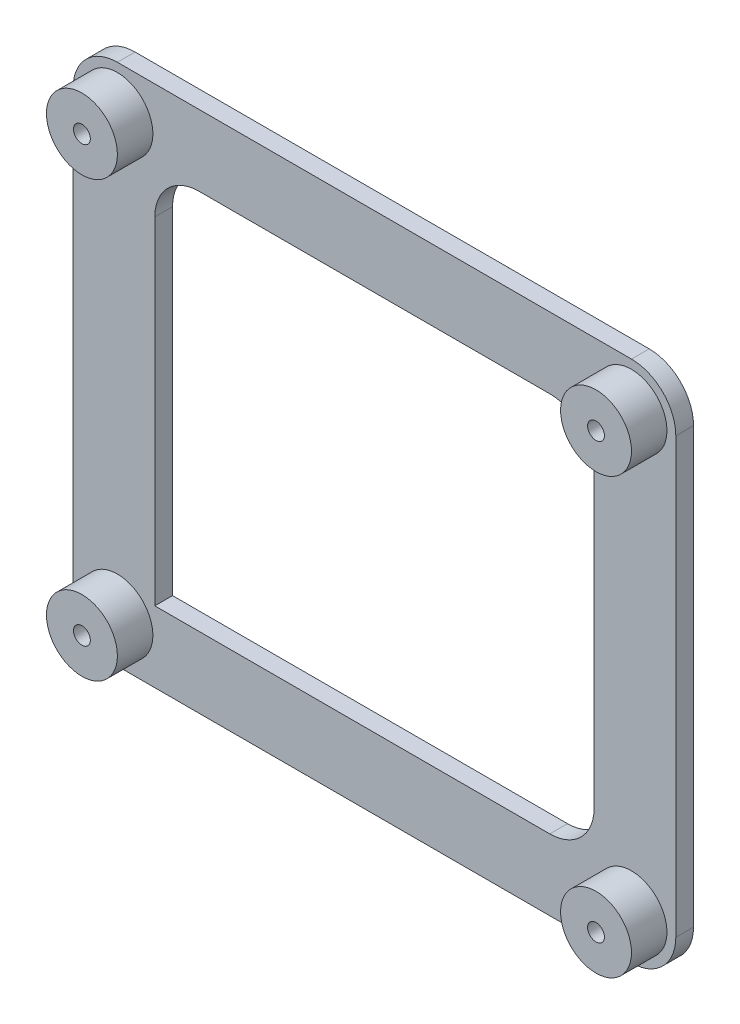
SolidWorks part; units mm, degrees
ref_plane "Front Plane" through (0, 0, 0) normal (0, 0, 1) x (1, 0, 0)
ref_plane "Top Plane" through (0, 0, 0) normal (0, 1, 0) x (1, 0, 0)
ref_plane "Right Plane" through (0, 0, 0) normal (1, 0, 0) x (0, 0, -1)
sketch "Sketch1" plane through (0, 0, 0) normal (0, 0, 1) x (1, 0, 0)
  line L1 (-29, -24.5) -> (29, -24.5) construction
  line L2 (-29, -24.5) -> (-29, 24.5) construction
  line L3 (-29, 24.5) -> (29, 24.5) construction
  line L4 (29, -24.5) -> (29, 24.5) construction
  line L5 (-29, -24.5) -> (29, 24.5) construction
  line L6 (-29, 24.5) -> (29, -24.5) construction
  line L7 (-34, -29.5) -> (34, -29.5)
  line L8 (-34, -29.5) -> (-34, 29.5)
  line L9 (-34, 29.5) -> (34, 29.5)
  line L10 (34, -29.5) -> (34, 29.5)
  line L11 (-34, -29.5) -> (34, 29.5) construction
  line L12 (-34, 29.5) -> (34, -29.5) construction
  line L13 (-24.7797, -21.5) -> (24.7797, -21.5)
  line L14 (-24.7797, -21.5) -> (-24.7797, 21.5)
  line L15 (-24.7797, 21.5) -> (24.7797, 21.5)
  line L16 (24.7797, -21.5) -> (24.7797, 21.5)
  line L17 (-24.7797, -21.5) -> (24.7797, 21.5) construction
  line L18 (-24.7797, 21.5) -> (24.7797, -21.5) construction
  circle A0 centre (-29, 24.5) radius 0.95
  circle A1 centre (29, 24.5) radius 0.95
  circle A2 centre (29, -24.5) radius 0.95
  circle A3 centre (-29, -24.5) radius 0.95
  point P0 (0, 0)
  point P6 (0, 0)
  point P11 (0, 0)
  dimension "D6" = 1.9
  dimension "D1" = 58
  dimension "D2" = 49
  dimension "D3" = 5
  dimension "D4" = 5
  dimension "D5" = 8
extrude "Boss-Extrude1" add sketch "Sketch1" along normal blind 2
sketch "Sketch2" plane through (0, 0, 2) normal (0, 0, 1) x (1, 0, 0)
  circle A0 centre (-29, 24.5) radius 4
  circle A1 centre (29, 24.5) radius 4
  circle A2 centre (29, -24.5) radius 4
  circle A3 centre (-29, -24.5) radius 4
  circle A4 centre (-29, -24.5) radius 0.95 construction
  circle A5 centre (29, -24.5) radius 0.95 construction
  circle A6 centre (29, 24.5) radius 0.95 construction
  circle A7 centre (-29, 24.5) radius 0.95 construction
  circle A8 centre (-29, -24.5) radius 0.95
  circle A9 centre (29, -24.5) radius 0.95
  circle A10 centre (29, 24.5) radius 0.95
  circle A11 centre (-29, 24.5) radius 0.95
  dimension "D1" = 8
extrude "Boss-Extrude2" add sketch "Sketch2" along normal blind 4
fillet "Fillet1" radius 5 7 edges at (24.7797, -21.5, 1) (24.7797, 21.5, 1) (-24.7797, 21.5, 1) (-34, 29.5, 1) (34, 29.5, 1) (34, -29.5, 1) (-34, -29.5, 1)
